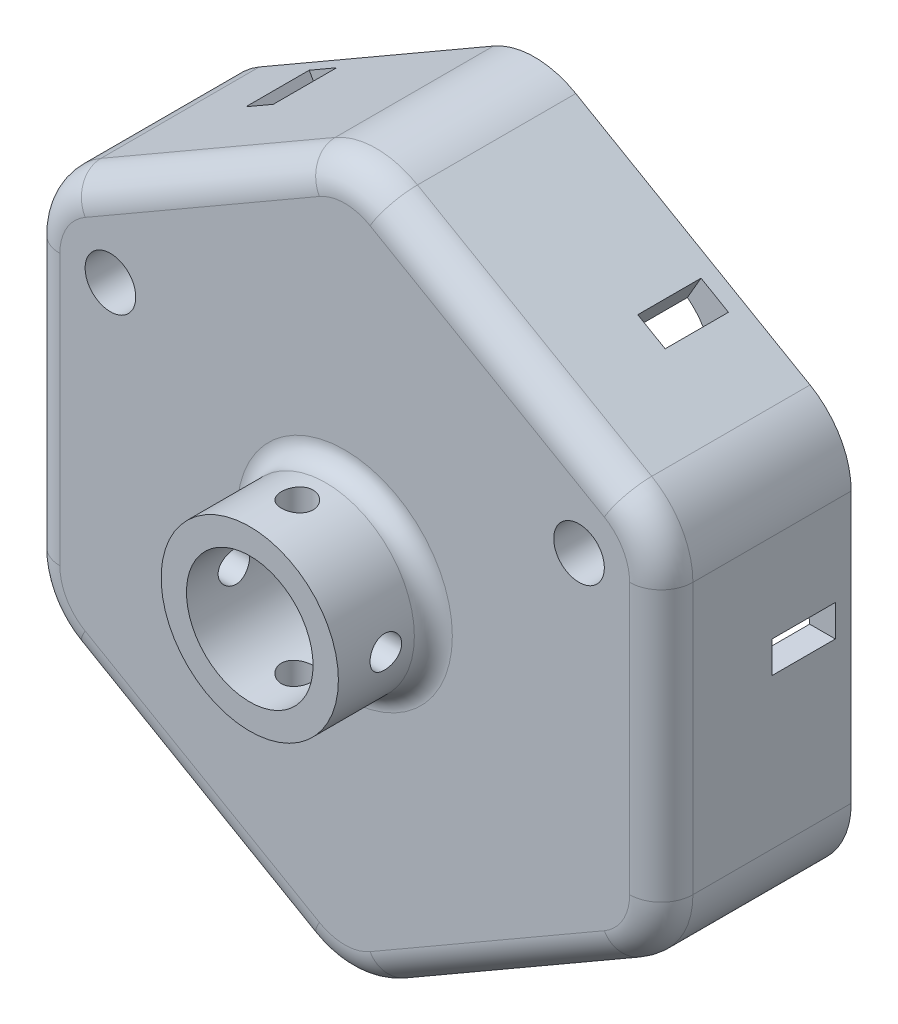
SolidWorks part; units mm, degrees
ref_plane "Front Plane" through (0, 0, 0) normal (0, 0, 1) x (1, 0, 0)
ref_plane "Top Plane" through (0, 0, 0) normal (0, 1, 0) x (1, 0, 0)
ref_plane "Right Plane" through (0, 0, 0) normal (1, 0, 0) x (0, 0, -1)
sketch "Sketch1" plane through (0, 0, 0) normal (0, 0, 1) x (1, 0, 0)
  line L0 (-50, 28.8675) -> (0, 0) construction
  line L1 (50, -28.8675) -> (50, 28.8675)
  line L2 (50, 28.8675) -> (0, 57.735)
  line L3 (0, 57.735) -> (-50, 28.8675)
  line L4 (-50, 28.8675) -> (-50, -28.8675)
  line L5 (-50, -28.8675) -> (0, -57.735)
  line L6 (0, -57.735) -> (50, -28.8675)
  line L7 (0, 0) -> (50, 28.8675) construction
  circle A0 centre (0, 0) radius 50 construction
  circle A1 centre (0, 0) radius 10
  circle A2 centre (-37.0096, 21.3675) radius 4
  circle A3 centre (37.0096, 21.3675) radius 4
  dimension "D1" = 100
  dimension "D2" = 20
  dimension "D3" = 15
  dimension "D5" = 8
  dimension "D4" = 15
extrude "Boss-Extrude1" add sketch "Sketch1" along normal blind 30
sketch "Sketch2" plane through (0, 0, 0) normal (0, 0, -1) x (-1, 0, 0)
  line L0 (-29.875, 29.6054) -> (-28.2419, 14.895) construction
  line L1 (-46, 2.4625) -> (-46, 11.2271) construction
  line L2 (-39.742, 13.2676) -> (-33.5746, 13.4822) construction
  line L3 (0, 0) -> (0, 53.1162) construction
  line L5 (-46, 26.5581) -> (-46, -26.5581) construction
  line L6 (-46, -26.5581) -> (0, -53.1162)
  line L7 (0, -53.1162) -> (46, -26.5581)
  line L8 (46, -26.5581) -> (46, 0)
  line L9 (23, 39.8372) -> (0, 53.1162)
  line L10 (0, 53.1162) -> (-23, 39.8372)
  line L11 (-46, 0) -> (-46, -26.5581)
  line L12 (-50, -28.8675) -> (0, -57.735)
  line L13 (0, -57.735) -> (50, -28.8675)
  line L14 (50, -28.8675) -> (50, 28.8675)
  line L15 (50, 28.8675) -> (0, 57.735)
  line L16 (0, 57.735) -> (-50, 28.8675)
  line L17 (-50, 28.8675) -> (-50, -28.8675)
  line L18 (-50, -28.8675) -> (0, -57.735)
  line L19 (0, -57.735) -> (50, -28.8675)
  line L20 (50, -28.8675) -> (50, 28.8675)
  line L21 (50, 28.8675) -> (0, 57.735)
  line L22 (0, 57.735) -> (-50, 28.8675)
  line L23 (-50, 28.8675) -> (-50, -28.8675)
  line L24 (-16.1587, 43.787) -> (-29.9538, 35.8224) construction
  line L25 (0, 53.1162) -> (-46, 26.5581) construction
  line L26 (46, 26.5581) -> (0, 53.1162) construction
  line L27 (46, -26.5581) -> (46, 26.5581) construction
  circle A0 centre (0, 0) radius 10 construction
  circle A1 centre (37.0096, 21.3675) radius 4 construction
  circle A2 centre (-37.0096, 21.3675) radius 4 construction
  circle A3 centre (0, 0) radius 10
  circle A4 centre (37.0096, 21.3675) radius 4
  circle A5 centre (-37.0096, 21.3675) radius 4
  circle A6 centre (-37.0096, 21.3675) radius 8
  circle A7 centre (0, 0) radius 14
  circle A8 centre (37.0096, 21.3675) radius 8
  spline S0 degree 3 poles (-29.0585, 22.2502) (-30.0791, 31.4442) (-32.1954, 34.5282) (-23, 39.8372) knots 0 0 0 0 1 1 1 1
  spline S1 degree 3 poles (-36.7315, 13.3724) (-45.8422, 13.0554) (-46, 3.6519) (-46, 0) knots 0 0 0 0 1 1 1 1
  spline S2 degree 3 poles (36.7315, 13.3724) (45.8422, 13.0554) (46, 3.6519) (46, 0) knots 0 0 0 0 1 1 1 1
  spline S3 degree 3 poles (29.0585, 22.2502) (30.0791, 31.4442) (32.1954, 34.5282) (23, 39.8372) knots 0 0 0 0 1 1 1 1
  dimension "D1" = 0
  dimension "D2" = 4
  dimension "D3" = 4
extrude "Cut-Extrude1" cut sketch "Sketch2" against normal blind 15 contours A8 S3 L9 L10 S0 A6 S1 L11 L6 L7 L8 S2 A7
sketch "Sketch3" plane through (0, 0, 15) normal (0, 0, -1) x (-1, 0, 0)
  line L0 (-46, -26.5581) -> (0, -53.1162) construction
  line L1 (-22.5, -20.3938) -> (22.5, -20.3938) construction
  line L2 (-22.5, -20.3938) -> (-22.5, -35.3938) construction
  line L3 (-22.5, -35.3938) -> (22.5, -35.3938) construction
  line L4 (22.5, -20.3938) -> (22.5, -35.3938) construction
  line L5 (-22.5, -20.3938) -> (22.5, -35.3938) construction
  line L6 (-22.5, -35.3938) -> (22.5, -20.3938) construction
  line L7 (0, -53.1162) -> (25.5, -38.3938)
  line L8 (-25.5, -17.3938) -> (-25.5, -38.3938)
  line L9 (-25.5, -38.3938) -> (25.5, -38.3938) construction
  line L10 (25.5, -17.3938) -> (25.5, -38.3938)
  line L11 (-25.5, -17.3938) -> (25.5, -17.3938)
  line L12 (0, -53.1162) -> (46, -26.5581) construction
  line L13 (-25.5, -38.3938) -> (0, -53.1162)
  point P0 (0, -27.8938)
  point P5 (0, 0)
  point P6 (0, 0)
  point P8 (0, 0)
  dimension "D1" = 15
  dimension "D2" = 45
  dimension "D3" = 3
extrude "Cut-Extrude2" cut sketch "Sketch3" against normal blind 10
fillet "Fillet1" radius 10 4 edges at (0, 53.1162, 7.5) (46, -26.5581, 7.5) (0, -53.1162, 12.5) (-46, -26.5581, 7.5)
sketch "Sketch4" plane through (0, 0, 30) normal (0, 0, 1) x (1, 0, 0)
  circle A0 centre (0, 0) radius 10 construction
  circle A1 centre (0, 0) radius 14 construction
  circle A2 centre (0, 0) radius 10
  circle A3 centre (0, 0) radius 14
extrude "Boss-Extrude2" add sketch "Sketch4" along normal blind 15
sketch "Sketch5" plane through (0, 0, 0) normal (1, 0, 0) x (0, 0, -1)
  line L0 (-45, 0) -> (-30, 0) construction
  line L1 (-45, 10) -> (-45, -10) construction
  line L2 (-30, -28.8675) -> (-30, 28.8675) construction
  line L3 (-15, 0) -> (0, 0) construction
  circle A0 centre (-37.5, 0) radius 2.5
  circle A1 centre (-7.5, 0) radius 2.5
  point P8 (-37.5, 0)
  dimension "D1" = 5
extrude "Cut-Extrude3" cut sketch "Sketch5" against normal mid plane 30
pattern_circular "CirPattern1" count 2 over 90 about axis through (0, 0, 45) along (0, 0, 1) of "Cut-Extrude3"
fillet "Fillet2" radius 3 2 edges at (-14, 0, 15) (14, 0, 30)
sketch "Sketch6" plane through (25, 43.3013, 0) normal (0.5, 0.866, 0) x (0.866, -0.5, 0)
  line L1 (4.3675, -12.5) -> (9.3675, -12.5)
  line L2 (4.3675, -12.5) -> (4.3675, -2.5)
  line L3 (4.3675, -2.5) -> (9.3675, -2.5)
  line L4 (9.3675, -12.5) -> (9.3675, -2.5)
  line L5 (4.3675, -12.5) -> (9.3675, -2.5) construction
  line L6 (4.3675, -2.5) -> (9.3675, -12.5) construction
  line L7 (25.3675, 0) -> (17.3675, 0) construction
  line L8 (25.3675, 0) -> (17.3675, 0) construction
  line L10 (28.8675, 0) -> (-28.8675, 0) construction
  point P0 (6.8675, -7.5)
  point P5 (0, 0)
  point P10 (0, 0)
  point P11 (14.3675, 0)
  dimension "D1" = 10
  dimension "D2" = 5
  dimension "D3" = 8
  dimension "D4" = 2.5
extrude "Cut-Extrude4" cut sketch "Sketch6" against normal blind 10
sketch "Sketch7" plane through (50, 0, 0) normal (1, 0, 0) x (0, 0, -1)
  line L0 (0, -28.8675) -> (0, 28.8675) construction
  line L1 (-12.5, 7.3675) -> (-2.5, 7.3675)
  line L2 (-12.5, 7.3675) -> (-12.5, 2.3675)
  line L3 (-12.5, 2.3675) -> (-2.5, 2.3675)
  line L4 (-2.5, 7.3675) -> (-2.5, 2.3675)
  line L5 (-12.5, 7.3675) -> (-2.5, 2.3675) construction
  line L6 (-12.5, 2.3675) -> (-2.5, 7.3675) construction
  line L7 (0, 17.3675) -> (0, 25.3675) construction
  line L8 (0, 17.3675) -> (0, 25.3675) construction
  point P0 (-7.5, 4.8675)
  dimension "D1" = 5
  dimension "D2" = 10
  dimension "D3" = 2.5
  dimension "D4" = 10
extrude "Cut-Extrude5" cut sketch "Sketch7" against normal blind 10
mirror "Mirror1" about plane through (0, 0, 0) normal (1, 0, 0) of "Cut-Extrude5", "Cut-Extrude4"
fillet "Fillet3" radius 13 6 edges at (-50, 28.8675, 15) (-50, -28.8675, 15) (0, -57.735, 15) (50, -28.8675, 15) (50, 28.8675, 15) (0, 57.735, 15)
fillet "Fillet4" radius 5 12 edges at (48.2583, 27.862, 30) (50, 0, 30) (48.2583, -27.862, 30) (25, -43.3013, 30) (0, -55.7239, 30) (-25, -43.3013, 30) (-48.2583, -27.862, 30) (-50, 0, 30) (-48.2583, 27.862, 30) (-25, 43.3013, 30) (0, 55.7239, 30) (25, 43.3013, 30)
